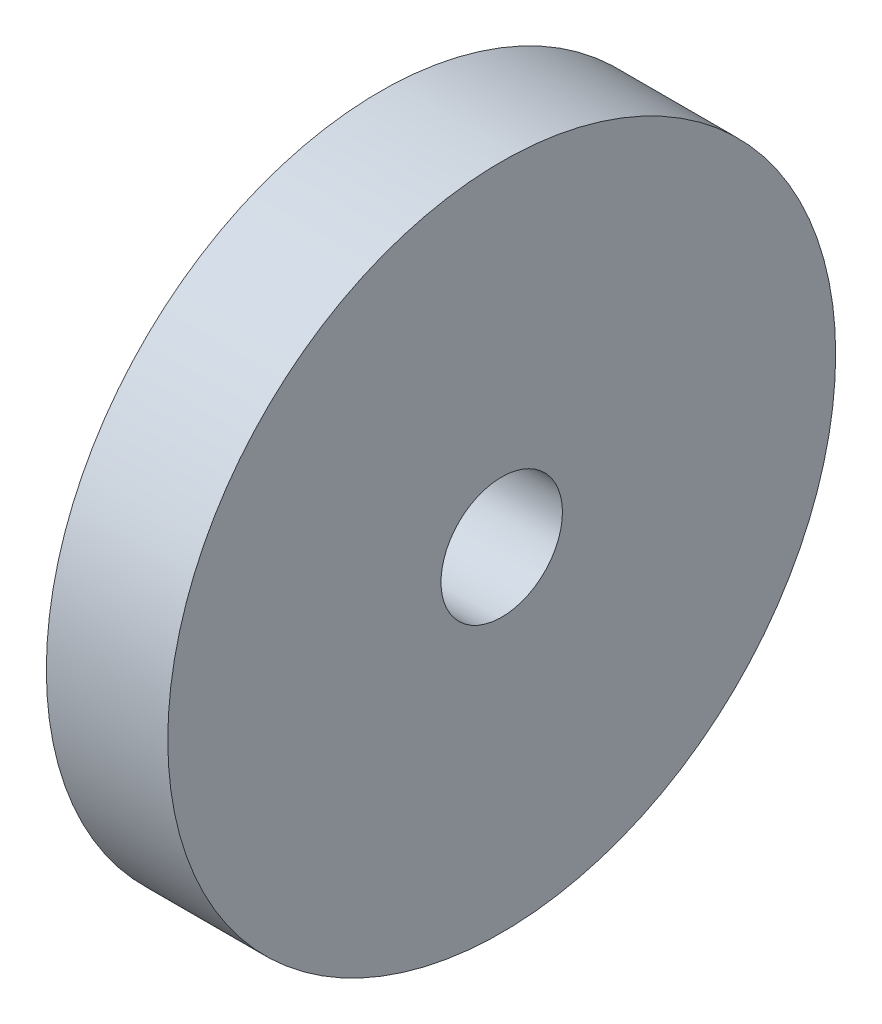
SolidWorks part; units mm, degrees
ref_plane "Front Plane" through (0, 0, 0) normal (0, 0, 1) x (1, 0, 0)
ref_plane "Top Plane" through (0, 0, 0) normal (0, 1, 0) x (1, 0, 0)
ref_plane "Right Plane" through (0, 0, 0) normal (1, 0, 0) x (0, 0, -1)
sketch "Sketch1" plane through (0, 0, 0) normal (1, 0, 0) x (0, 0, -1)
  circle A0 centre (0, 0) radius 5.5
  circle A1 centre (0, 0) radius 1
  dimension "D1" = 2
  dimension "D2" = 11
extrude "Boss-Extrude1" add sketch "Sketch1" along normal blind 2
